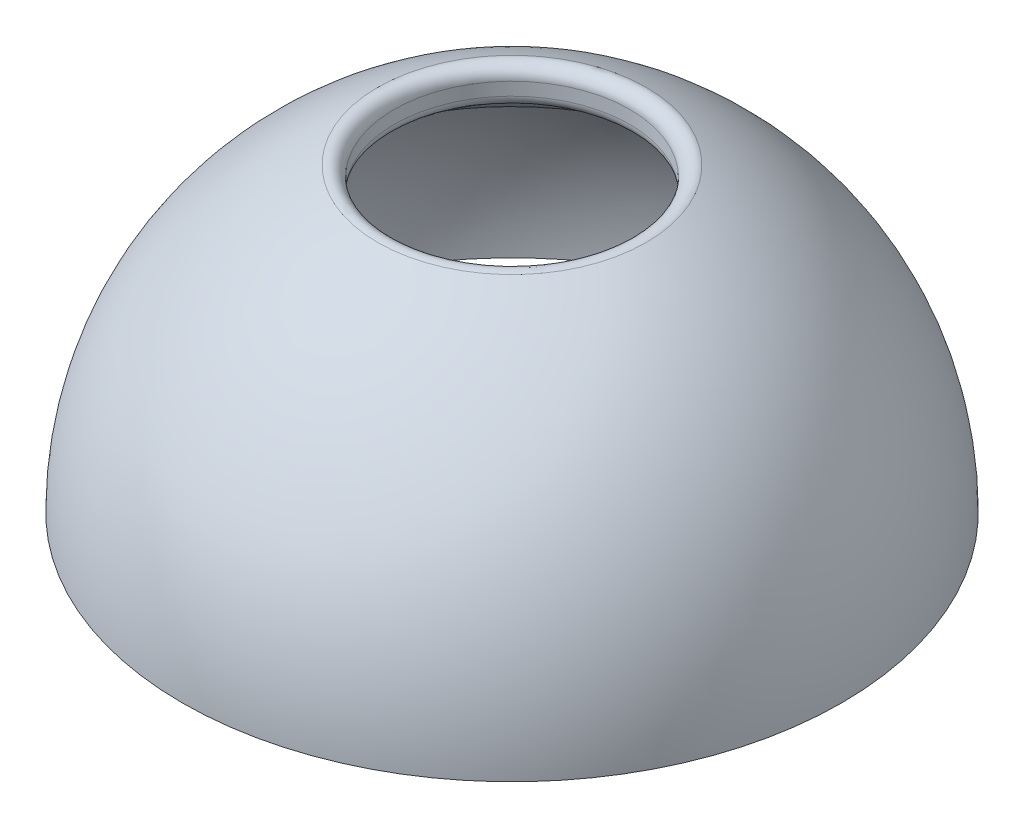
SolidWorks part; units mm, degrees
ref_plane "Alzado" through (0, 0, 0) normal (0, 0, 1) x (1, 0, 0)
ref_plane "Planta" through (0, 0, 0) normal (0, 1, 0) x (1, 0, 0)
ref_plane "Vista lateral" through (0, 0, 0) normal (1, 0, 0) x (0, 0, -1)
sketch "Croquis1" plane through (0, 0, 0) normal (1, 0, 0) x (0, 0, -1)
  line L0 (0, 29) -> (0, -28) construction
  line L1 (-0.5, 27.9955) -> (-0.5, 26.4953)
  line L2 (-19.1511, 16.0697) -> (0, 0) construction
  line L3 (-19.1511, 16.0697) -> (-20.3002, 17.0339)
  line L4 (-0.5, 26.4953) -> (-0.5, 24.995)
  line L5 (0, -26.5) -> (0, -28)
  arc A0 (-0.5, 27.9955) -> (0, -28) centre (0, 0) ccw
  arc A1 (-20.3002, 17.0339) -> (0, -26.5) centre (0, 0) ccw
  arc A2 (-19.1511, 16.0697) -> (-0.5, 24.995) centre (0, 0) cw
  arc A3 (-0.5, 26.4953) -> (-20.3002, 17.0339) centre (0, 0) ccw construction
  dimension "D1" = 56
  dimension "D2" = 53
  dimension "D5" = 1.5
  dimension "D3" = 0.5
  dimension "D4" = 50
revolve "Revolución3" add sketch "Croquis1" angle 360 about L0
sketch "Croquis2" plane through (0, 0, 0) normal (1, 0, 0) x (0, 0, -1)
  line L0 (0, 0) -> (0, 42.1069) construction
  line L1 (0, 30) -> (0, 16)
  line L2 (-10, 16) -> (0, 16)
  line L3 (-10, 16) -> (-10, 30)
  line L4 (-10, 30) -> (0, 30)
  line L5 (10, 16) -> (10, 30) construction
  line L6 (-10, 16) -> (10, 30) construction
  line L7 (-10, 30) -> (10, 16) construction
  line L8 (0, 30) -> (10, 30) construction
  line L9 (0, 16) -> (10, 16) construction
  point P3 (0, 23)
  dimension "D1" = 20
  dimension "D2" = 14
  dimension "D3" = 23
revolve "Cortar-Revolución2" cut sketch "Croquis2" angle 360 about L0
fillet "Redondeo1" radius 1 3 edges at (0, 26.1534, -10) (0, 16.0697, 19.1511) (0, 22.9129, -10)
sketch "Croquis3" plane through (0, 0, 0) normal (0, 1, 0) x (1, 0, 0)
  circle A0 centre (0, 0) radius 29.8457
extrude "Cortar-Extruir1" cut sketch "Croquis3" against normal blind 30
ref_plane "Plano1" through (0, 25.5709, 0) normal (0, 1, 0) x (1, 0, 0)
sketch "Croquis4" plane through (0, 25.5709, 0) normal (0, 1, 0) x (1, 0, 0)
  circle A0 centre (0, 0) radius 15
  circle A1 centre (0, 0) radius 17.5
  circle A2 centre (0, 0) radius 20
  circle A3 centre (0, 0) radius 22.5
  circle A4 centre (0, 0) radius 24
  circle A5 centre (0, 0) radius 26.5
  dimension "D1" = 30
  dimension "D2" = 35
  dimension "D3" = 40
  dimension "D4" = 45
  dimension "D5" = 48
  dimension "D6" = 53
extrude "Extruir-Lámina1" [suppressed] add sketch "Croquis4" against normal up to surface (2.0882 mm away) thin contours A0 | A1 | A2 | A3 | A4 | A5
